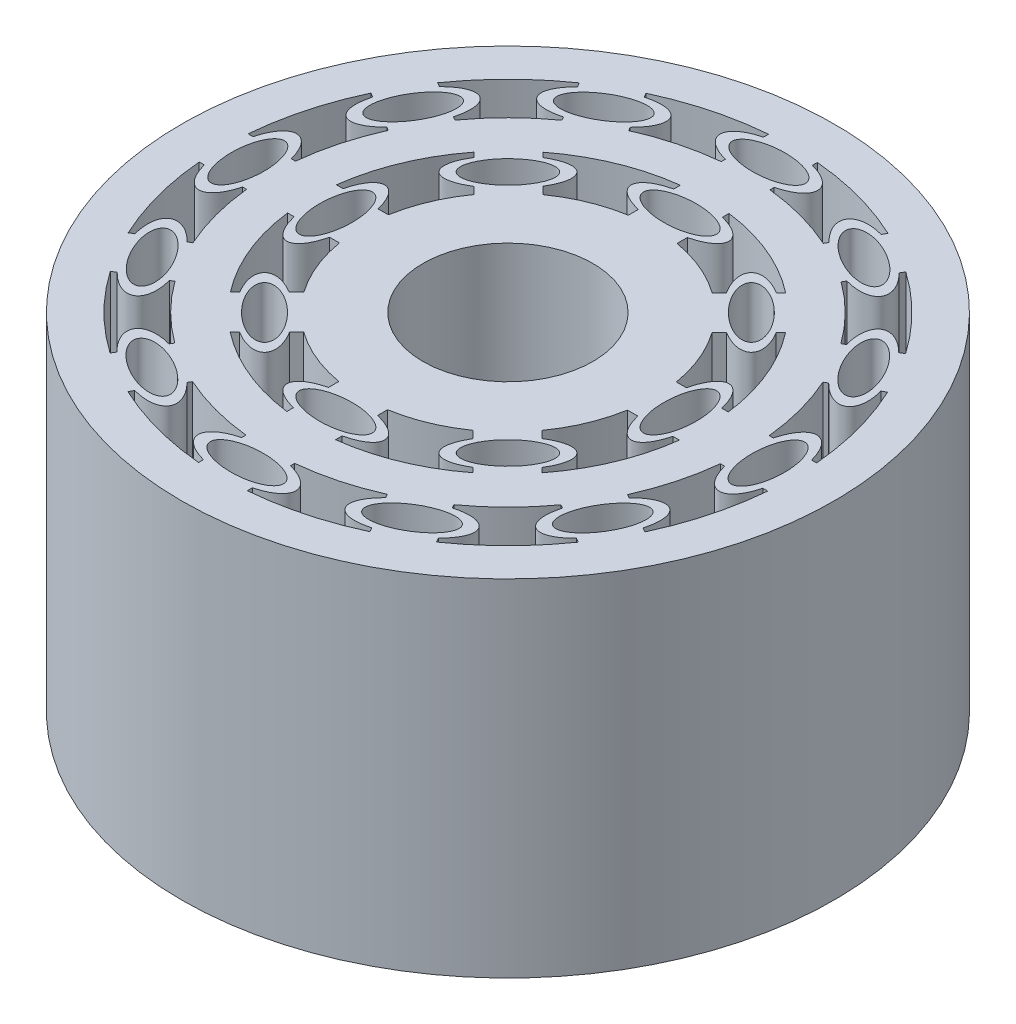
SolidWorks part; units mm, degrees
material "Silicon"
ref_plane "Front Plane" through (0, 0, 0) normal (0, 0, 1) x (1, 0, 0)
ref_plane "Top Plane" through (0, 0, 0) normal (0, 1, 0) x (1, 0, 0)
ref_plane "Right Plane" through (0, 0, 0) normal (1, 0, 0) x (0, 0, -1)
sketch "Sketch1" plane through (0, 0, 0) normal (0, 1, 0) x (1, 0, 0)
  circle A0 centre (0, 0) radius 40.125
  dimension "D1" = 80.25
extrude "Boss-Extrude1" add sketch "Sketch1" along normal blind 42.5 contours A0
sketch "Sketch2" plane through (0, 42.5, 0) normal (0, 1, 0) x (1, 0, 0)
  circle A0 centre (0, 0) radius 35.125
  circle A1 centre (0, 0) radius 40.125 construction
  dimension "D1" = 5
extrude "Cut-Extrude1" cut sketch "Sketch2" against normal through all
sketch "Sketch3" plane through (0, 0, 0) normal (0, 1, 0) x (1, 0, 0)
  circle A0 centre (0, 0) radius 29.325
  dimension "D1" = 58.65
extrude "Boss-Extrude2" add sketch "Sketch3" along normal through all separate body
sketch "Sketch4" plane through (0, 42.5, 0) normal (0, 1, 0) x (1, 0, 0)
  circle A0 centre (0, 0) radius 24.325
  dimension "D1" = 48.65
extrude "Cut-Extrude2" cut sketch "Sketch4" against normal through all
sketch "Sketch5" plane through (0, 42.5, 0) normal (0, 1, 0) x (1, 0, 0)
  line L2 (-2.9525, 34.3816) -> (-2.9525, 35.745)
  line L3 (-2.9525, 35.745) -> (3.0475, 35.745)
  line L4 (3.0475, 34.3816) -> (3.0475, 35.745)
  line L7 (-2.9525, 29.6834) -> (-2.9525, 28.32)
  line L9 (3.0475, 29.6834) -> (3.0475, 28.32)
  line L10 (-2.9525, 28.32) -> (3.0475, 28.32)
  ellipse E0 centre (0.0475, 32.0325) end of major axis (-5.9525, 32.0325) minor radius 2.7125 (-2.9525, 34.3816) -> (-2.9525, 29.6834) ccw
  ellipse E1 centre (0.0475, 32.0325) end of major axis (-5.9525, 32.0325) minor radius 2.7125 (3.0475, 29.6834) -> (3.0475, 34.3816) ccw
  point P0 (0.0475, 34.745)
  dimension "D1" = 12
  dimension "D2" = 5.425
  dimension "D3" = 6
extrude "Boss-Extrude6" add sketch "Sketch5" against normal through all contours E0 L7 L10 L9 E1 L4 L3 L2
sketch "Sketch10" plane through (0, 42.5, 0) normal (0, 1, 0) x (1, 0, 0)
  ellipse E0 centre (0.0475, 32.0325) end of major axis (-4.4525, 32.0325) minor radius 2
  dimension "D1" = 4
  dimension "D2" = 9
extrude "Cut-Extrude4" cut sketch "Sketch10" against normal through all
pattern_circular "CirPattern11" count 12 over 360 of "Cut-Extrude4", "Boss-Extrude6"
sketch "Sketch14" plane through (0, 42.5, 0) normal (0, 1, 0) x (1, 0, 0)
  circle A0 centre (0, 0) radius 18
  dimension "D1" = 36
extrude "Boss-Extrude7" add sketch "Sketch14" against normal up to surface (42.5 mm away) up to face at (-29.9672, 0, -12.1602)
sketch "Sketch31" plane through (0, 42.5, 0) normal (0, 1, 0) x (1, 0, 0)
  line L7 (-4.4525, 32.0325) -> (-4.4525, 13.6525) construction
  line L8 (4.5475, 32.0325) -> (4.5475, 13.6525) construction
  line L9 (-2.9525, 25.0863) -> (3.0475, 25.0863)
  line L10 (3.0475, 25.0863) -> (3.0475, 23.316)
  line L11 (-2.9525, 25.0863) -> (-2.9525, 23.3389)
  line L12 (-2.9525, 16.7822) -> (3.0475, 16.7822)
  line L13 (3.0475, 16.7822) -> (3.0475, 19.009)
  line L14 (-2.9525, 16.7822) -> (-2.9525, 18.9861)
  ellipse E2 centre (0.0475, 32.0325) end of major axis (-4.4525, 32.0325) minor radius 2 construction
  ellipse E3 centre (0, 21.1625) end of major axis (-6, 21.1625) minor radius 2.5 (-2.9525, 23.3389) -> (-2.9525, 18.9861) ccw
  ellipse E4 centre (0, 21.1625) end of major axis (-6, 21.1625) minor radius 2.5 (3.0475, 19.009) -> (3.0475, 23.316) ccw
  point P34 (0, 21.1625)
  dimension "D1" = 6
  dimension "D2" = 6
  dimension "D3" = 12
  dimension "D4" = 5
extrude "Boss-Extrude11" add sketch "Sketch31" against normal through all contours E3 L14 L12 L13 E4 L10 L9 L11
sketch "Sketch32" plane through (0, 42.5, 0) normal (0, 1, 0) x (1, 0, 0)
  ellipse E0 centre (0, 21.1625) end of major axis (-4.5, 21.1625) minor radius 2
  dimension "D1" = 4
  dimension "D2" = 9
extrude "Cut-Extrude10" cut sketch "Sketch32" against normal through all
pattern_circular "CirPattern12" count 8 over 360 of "Cut-Extrude10", "Boss-Extrude11"
sketch "Sketch33" plane through (0, 42.5, 0) normal (0, 1, 0) x (1, 0, 0)
  circle A0 centre (0, 0) radius 10.45
  dimension "D1" = 20.9
extrude "Cut-Extrude11" cut sketch "Sketch33" against normal through all
sketch "Sketch34" plane through (0, 0, 0) normal (0, -1, 0) x (-1, 0, 0)
  circle A0 centre (0, 0) radius 11
extrude "Boss-Extrude12" add sketch "Sketch34" against normal blind 2
